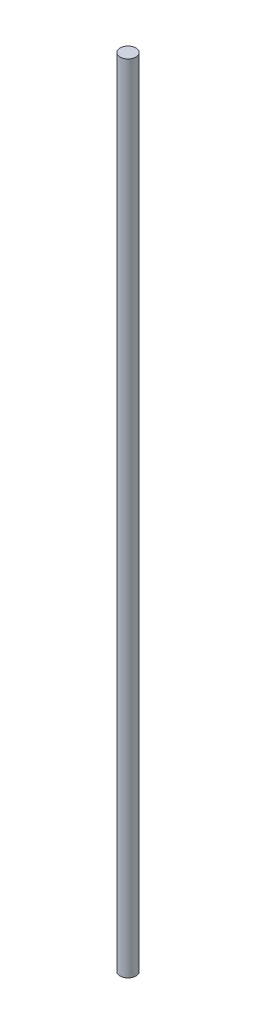
SolidWorks part; units mm, degrees
ref_plane "Alzado" through (0, 0, 0) normal (0, 0, 1) x (1, 0, 0)
ref_plane "Planta" through (0, 0, 0) normal (0, 1, 0) x (1, 0, 0)
ref_plane "Vista lateral" through (0, 0, 0) normal (1, 0, 0) x (0, 0, -1)
sketch "Croquis1" plane through (0, 0, 0) normal (0, 1, 0) x (1, 0, 0)
  circle A0 centre (0, 0) radius 2.5
  dimension "D1" = 5
extrude "Saliente-Extruir1" add sketch "Croquis1" along normal blind 250
